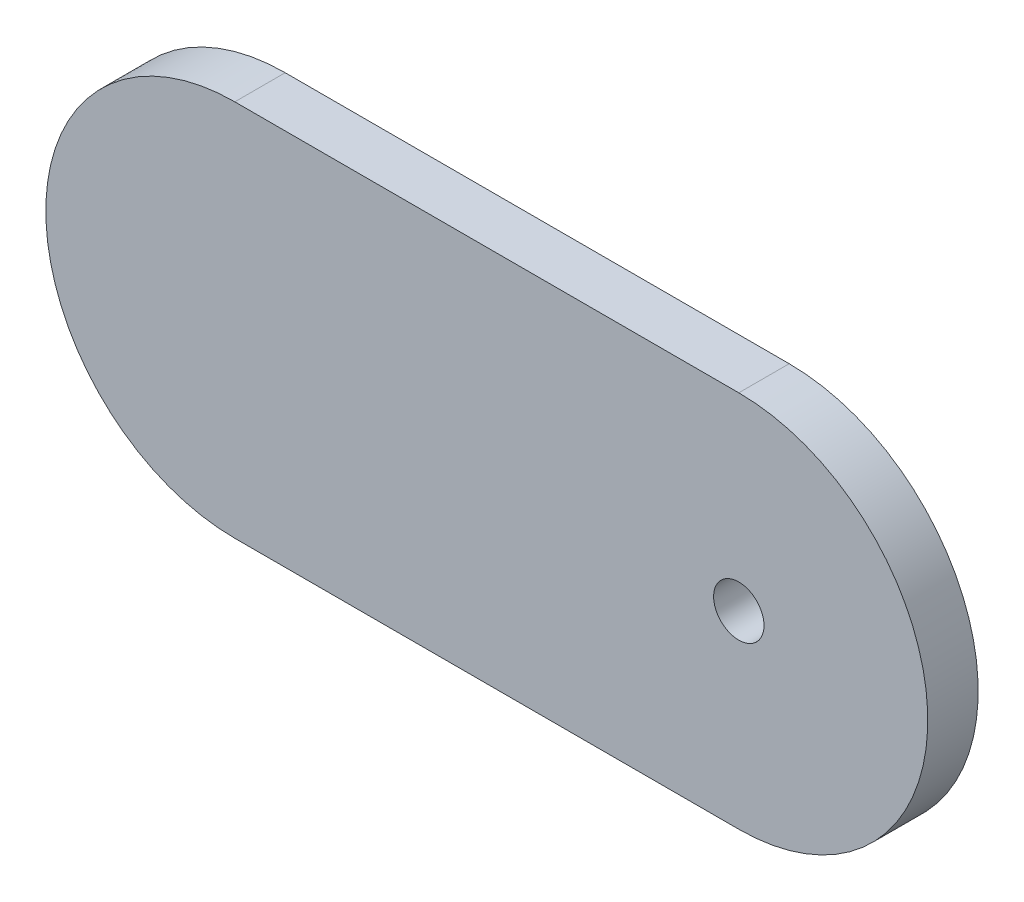
SolidWorks part; units mm, degrees
ref_plane "Plan de face" through (0, 0, 0) normal (0, 0, 1) x (1, 0, 0)
ref_plane "Plan de dessus" through (0, 0, 0) normal (0, 1, 0) x (1, 0, 0)
ref_plane "Plan de droite" through (0, 0, 0) normal (1, 0, 0) x (0, 0, -1)
sketch "Esquisse1" plane through (0, 0, 0) normal (0, 0, 1) x (1, 0, 0)
  line L0 (0, 0) -> (40, 0) construction
  line L1 (0, 15) -> (40, 15)
  line L2 (0, -15) -> (40, -15)
  arc A0 (0, 15) -> (0, -15) centre (0, 0) ccw
  arc A1 (40, -15) -> (40, 15) centre (40, 0) ccw
  circle A2 centre (40, 0) radius 2
  point P3 (20, 0)
  point P8 (-15, 0)
  dimension "D1" = 40
  dimension "D3" = 4
  dimension "D2" = 15
extrude "Boss.-Extru.1" add sketch "Esquisse1" along normal blind 4
